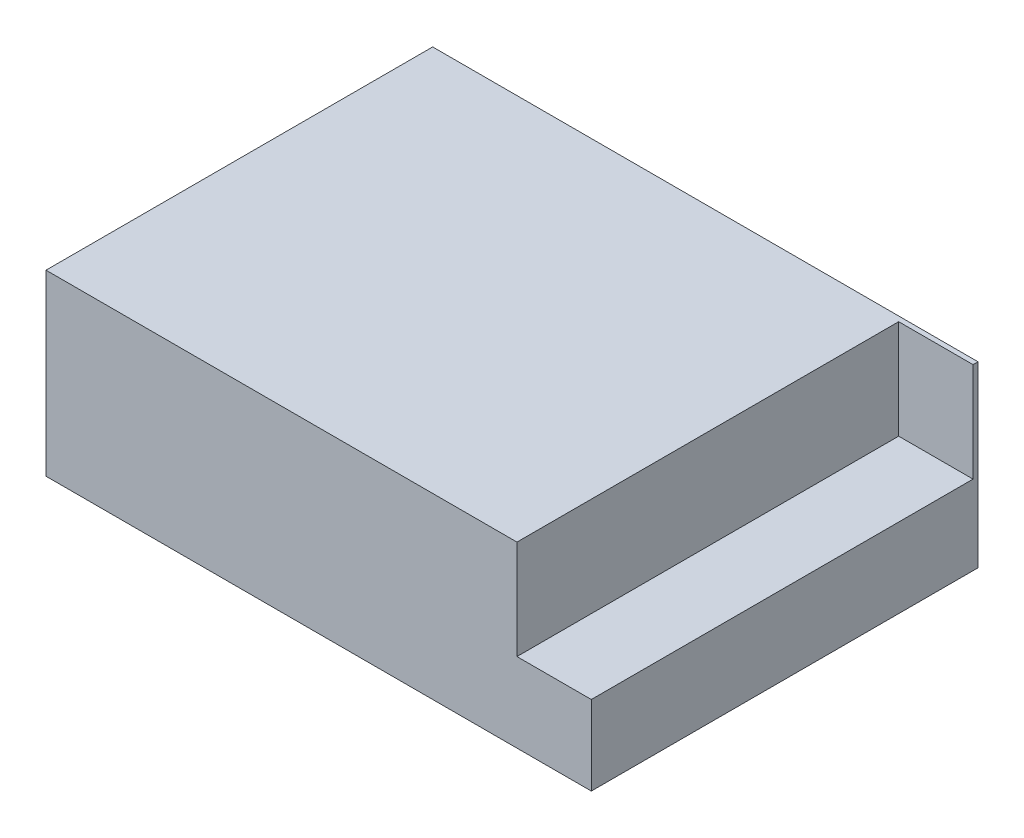
SolidWorks part; units mm, degrees
ref_plane "Front Plane" through (0, 0, 0) normal (0, 0, 1) x (1, 0, 0)
ref_plane "Top Plane" through (0, 0, 0) normal (0, 1, 0) x (1, 0, 0)
ref_plane "Right Plane" through (0, 0, 0) normal (1, 0, 0) x (0, 0, -1)
sketch "Sketch1" plane through (0, 0, 0) normal (0, 1, 0) x (1, 0, 0)
  line L1 (0, 0) -> (110, 0)
  line L2 (0, 0) -> (0, 78)
  line L3 (0, 78) -> (110, 78)
  line L4 (110, 0) -> (110, 78)
  dimension "D1" = 110
  dimension "D2" = 78
extrude "Boss-Extrude1" add sketch "Sketch1" along normal blind 36
sketch "Sketch2" plane through (0, 0, 0) normal (0, 0, 1) x (1, 0, 0)
  line L0 (0, 36) -> (110, 36) construction
  line L1 (95, 36) -> (110, 36)
  line L2 (95, 36) -> (95, 16)
  line L3 (95, 16) -> (110, 16)
  line L4 (110, 36) -> (110, 16)
  line L5 (110, 36) -> (110, 0) construction
  dimension "D1" = 15
  dimension "D2" = 20
extrude "Cut-Extrude1" cut sketch "Sketch2" against normal blind 77
